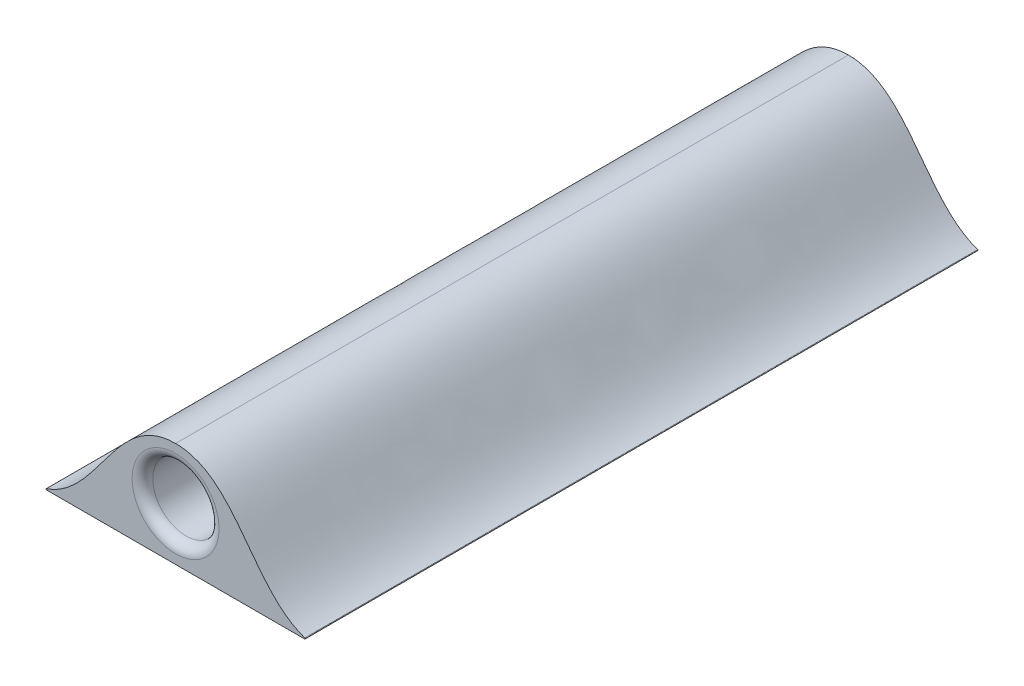
SolidWorks part; units mm, degrees
ref_plane "Front Plane" through (0, 0, 0) normal (0, 0, 1) x (1, 0, 0)
ref_plane "Top Plane" through (0, 0, 0) normal (0, 1, 0) x (1, 0, 0)
ref_plane "Right Plane" through (0, 0, 0) normal (1, 0, 0) x (0, 0, -1)
sketch "Sketch1" plane through (0, 0, 0) normal (0, 0, 1) x (1, 0, 0)
  line L0 (-6.5, -2.5852) -> (6.5, -2.5852)
  line L1 (0, 0) -> (0, -2.5852) construction
  line L2 (0, 2.5557) -> (1.9795, 2.5557) construction
  circle A0 centre (0, 0) radius 1.625
  spline S0 degree 3 poles (-6.5, -2.5852) (-3.7607, -1.8282) (-3.0367, 2.5557) (0, 2.5557) knots 0 0 0 0 1 1 1 1
  spline S1 degree 3 poles (6.5, -2.5852) (3.7607, -1.8282) (3.0367, 2.5557) (0, 2.5557) knots 0 0 0 0 1 1 1 1
  point P7 (-4.7273, -1.433)
  dimension "D1" = 3.25
  dimension "D2" = 13
extrude "Boss-Extrude1" add sketch "Sketch1" along normal blind 33
sketch "Sketch2" plane through (0, -2.5852, 0) normal (0, -1, 0) x (1, 0, 0)
  line L8 (-5.357, 1.143) -> (5.357, 1.143)
  line L9 (5.357, 1.143) -> (5.357, 31.857)
  line L10 (5.357, 31.857) -> (-5.357, 31.857)
  line L11 (-5.357, 31.857) -> (-5.357, 1.143)
  line L12 (-5.357, 1.143) -> (5.357, 1.143)
  line L13 (5.357, 1.143) -> (5.357, 31.857)
  line L14 (5.357, 31.857) -> (-5.357, 31.857)
  line L15 (-5.357, 31.857) -> (-5.357, 1.143)
  dimension "D1" = 1.143
extrude "Cut-Extrude1" cut sketch "Sketch2" against normal blind 0.5
fillet "Fillet1" radius 0.0254 2 edges at (-6.5, -2.5852, 16.5) (6.5, -2.5852, 16.5)
fillet "Fillet2" radius 0.508 2 edges at (1.625, 0, 0) (1.625, 0, 33)
